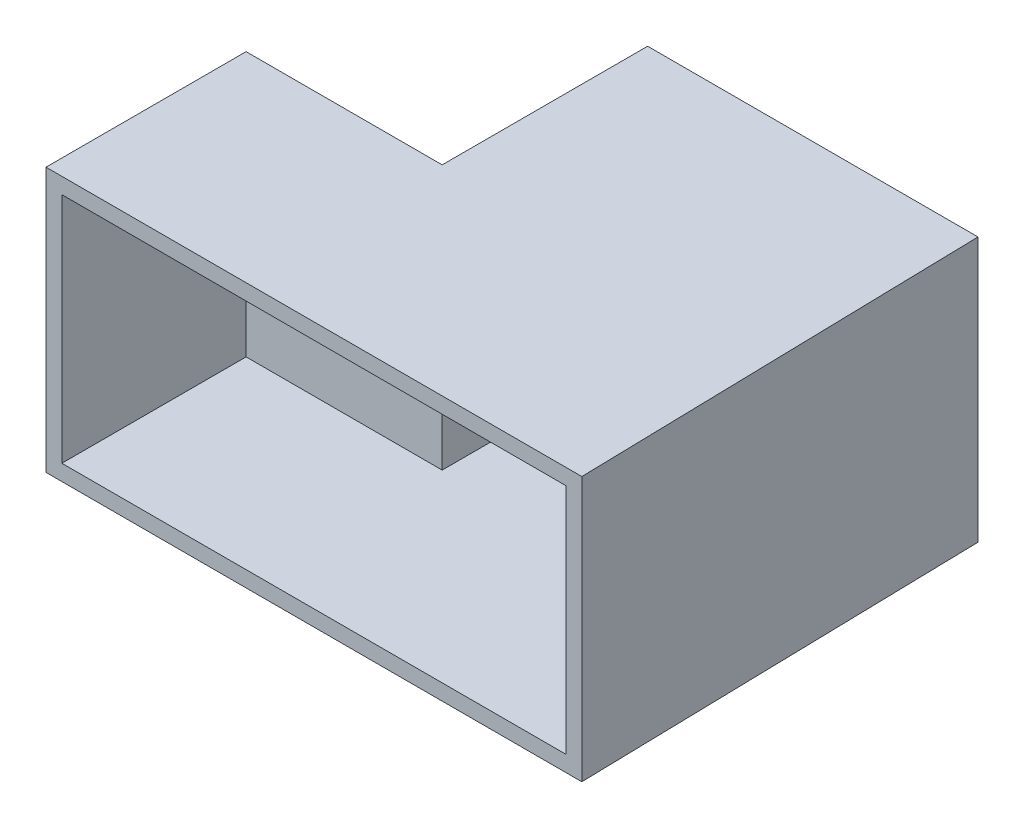
SolidWorks part; units mm, degrees
ref_plane "Front Plane" through (0, 0, 0) normal (0, 0, 1) x (1, 0, 0)
ref_plane "Top Plane" through (0, 0, 0) normal (0, 1, 0) x (1, 0, 0)
ref_plane "Right Plane" through (0, 0, 0) normal (1, 0, 0) x (0, 0, -1)
sketch "Sketch1" plane through (0, 0, 0) normal (0, 1, 0) x (1, 0, 0)
  line L0 (-25.019, 12.954) -> (-25.019, -25.908)
  line L1 (-25.019, -25.908) -> (-62.103, -25.908)
  line L2 (-62.103, -25.908) -> (-62.103, -63.754)
  line L3 (-62.103, -63.754) -> (39.243, -63.754)
  line L4 (39.243, -63.754) -> (37.465, 12.954)
  line L5 (37.465, 12.954) -> (-25.019, 12.954)
extrude "Boss-Extrude1" add sketch "Sketch1" along normal blind 50
shell "Shell1" thickness 3
